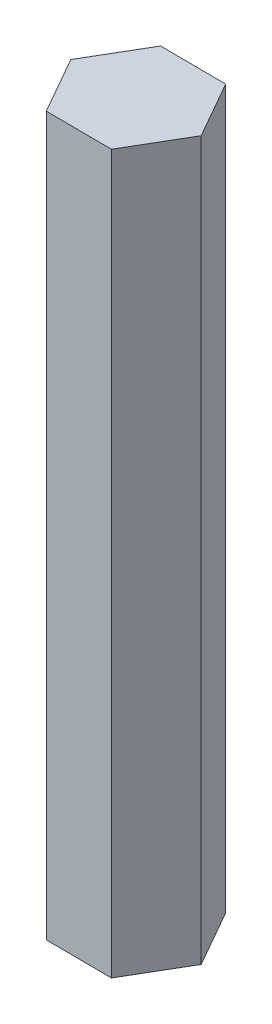
SolidWorks part; units mm, degrees
material "ASTM A36 Steel"
ref_plane "Front Plane" through (0, 0, 0) normal (0, 0, 1) x (1, 0, 0)
ref_plane "Top Plane" through (0, 0, 0) normal (0, 1, 0) x (1, 0, 0)
ref_plane "Right Plane" through (0, 0, 0) normal (1, 0, 0) x (0, 0, -1)
sketch "Sketch1" plane through (0, 0, 0) normal (0, 1, 0) x (1, 0, 0)
  line L1 (4.8008, 8.1977) -> (-4.699, 8.2565)
  line L2 (-4.699, 8.2565) -> (-9.4998, 0.0588)
  line L3 (-9.4998, 0.0588) -> (-4.8008, -8.1977)
  line L4 (-4.8008, -8.1977) -> (4.699, -8.2565)
  line L5 (4.699, -8.2565) -> (9.4998, -0.0588)
  line L6 (9.4998, -0.0588) -> (4.8008, 8.1977)
  circle A0 centre (0, 0) radius 8.2272 construction
  dimension "D1" = 19
extrude "Boss-Extrude1" add sketch "Sketch1" along normal blind 104
